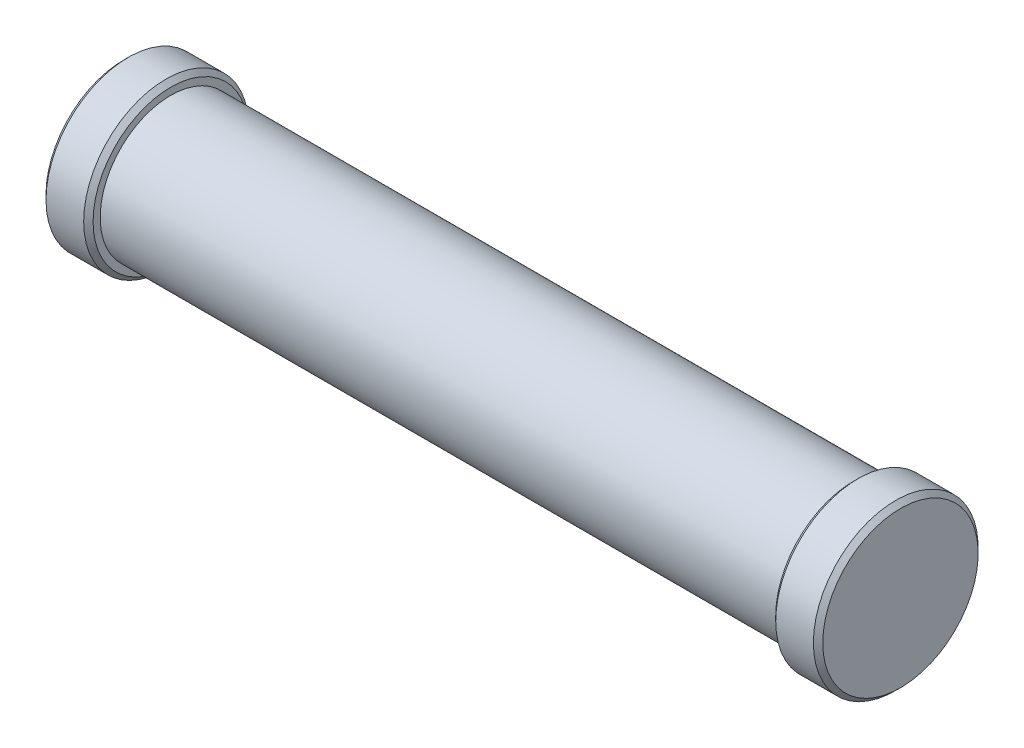
SolidWorks part; units mm, degrees
ref_plane "Front Plane" through (0, 0, 0) normal (0, 0, 1) x (1, 0, 0)
ref_plane "Top Plane" through (0, 0, 0) normal (0, 1, 0) x (1, 0, 0)
ref_plane "Right Plane" through (0, 0, 0) normal (1, 0, 0) x (0, 0, -1)
sketch "Sketch1" plane through (0, 0, 0) normal (1, 0, 0) x (0, 0, -1)
  circle A0 centre (0, 0) radius 30
  dimension "D1" = 60
extrude "Boss-Extrude1" add sketch "Sketch1" along normal mid plane 290
sketch "Sketch2" plane through (-145, 0, 0) normal (-1, 0, 0) x (0, 0, 1)
  circle A2 centre (0, 0) radius 35
  circle A3 centre (0, 0) radius 35
  dimension "D1" = 5
extrude "Boss-Extrude2" add sketch "Sketch2" along normal blind 20 separate body
chamfer "Chamfer1" distance 2 angle 45 2 edges at (-145, 0, 35) (-165, 0, 35)
mirror "Mirror1" about plane through (0, 0, 0) normal (1, 0, 0) of bodies 102
